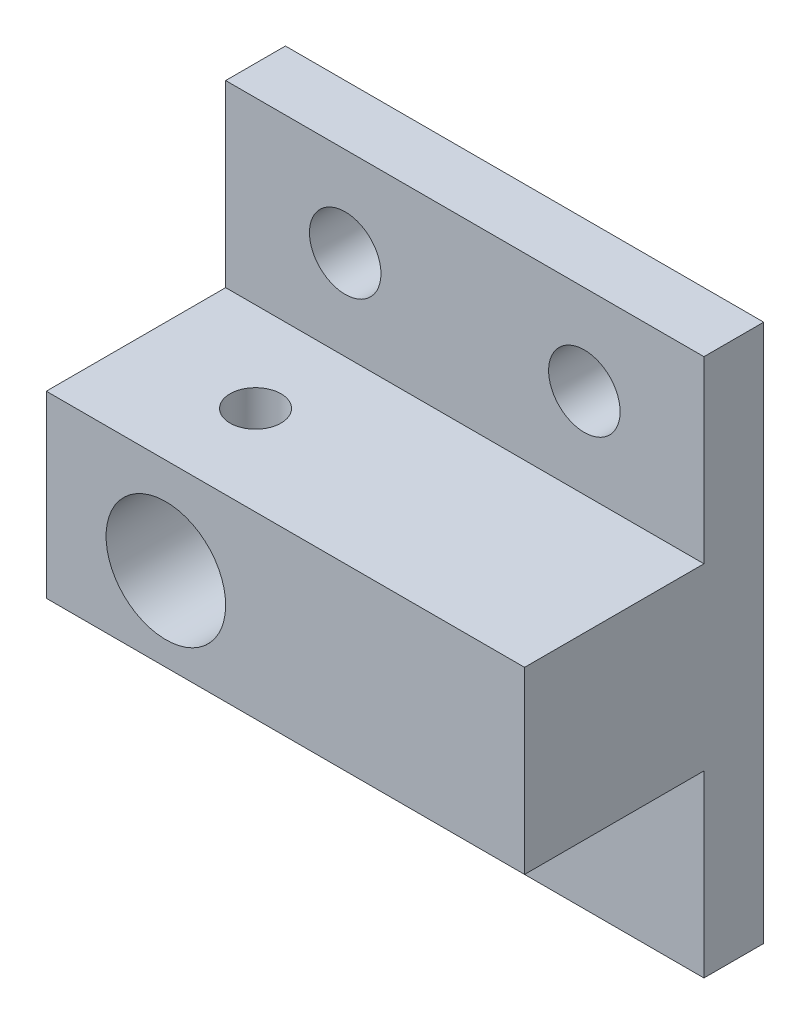
SolidWorks part; units mm, degrees
material "6061 Alloy"
ref_plane "Front Plane" through (0, 0, 0) normal (0, 0, 1) x (1, 0, 0)
ref_plane "Top Plane" through (0, 0, 0) normal (0, 1, 0) x (1, 0, 0)
ref_plane "Right Plane" through (0, 0, 0) normal (1, 0, 0) x (0, 0, -1)
sketch "Sketch1" plane through (0, 0, 0) normal (0, 0, 1) x (1, 0, 0)
  line L1 (-12.7, -14.2875) -> (12.7, -14.2875)
  line L2 (-12.7, -14.2875) -> (-12.7, 14.2875)
  line L3 (-12.7, 14.2875) -> (12.7, 14.2875)
  line L4 (12.7, -14.2875) -> (12.7, 14.2875)
  line L5 (-12.7, -14.2875) -> (12.7, 14.2875) construction
  line L6 (-12.7, 14.2875) -> (12.7, -14.2875) construction
  point P0 (0, 0)
  dimension "D1" = 25.4
  dimension "D2" = 28.575
extrude "Boss-Extrude1" add sketch "Sketch1" along normal blind 12.7
sketch "Sketch3" plane through (0, 0, 12.7) normal (0, 0, 1) x (1, 0, 0)
  line L0 (0, -55) -> (0, 55) construction
  line L1 (-12.7, 4.7625) -> (12.7, 4.7625)
  line L2 (-12.7, 4.7625) -> (-12.7, 14.2875)
  line L3 (-12.7, 14.2875) -> (12.7, 14.2875)
  line L4 (12.7, 4.7625) -> (12.7, 14.2875)
  line L5 (-12.7, 4.7625) -> (12.7, 14.2875) construction
  line L6 (-12.7, 14.2875) -> (12.7, 4.7625) construction
  line L9 (-12.7, -4.7625) -> (12.7, -4.7625)
  line L10 (-12.7, -4.7625) -> (-12.7, -14.2875)
  line L11 (-12.7, -14.2875) -> (12.7, -14.2875)
  line L12 (12.7, -4.7625) -> (12.7, -14.2875)
  line L13 (-12.7, -4.7625) -> (12.7, -14.2875) construction
  line L14 (-12.7, -14.2875) -> (12.7, -4.7625) construction
  point P0 (0, 9.525)
  point P5 (0, -9.525)
  line M2 (12.7, -14.2875) -> (12.7, 14.2875)
  line M4 (-12.7, 14.2875) -> (-12.7, -14.2875)
  line M5 (-12.7, -14.2875) -> (12.7, -14.2875)
  dimension "D1" = 9.525
  dimension "D2" = 9.525
extrude "Cut-Extrude1" cut sketch "Sketch3" against normal blind 9.525 contours L9 M4 M5 M2 | L1 L4 L3 L2
sketch "Sketch2" plane through (0, 0, 12.7) normal (0, 0, 1) x (1, 0, 0)
  line L2 (-12.7, 4.7625) -> (-12.7, -4.7625) construction
  line L3 (-12.7, 4.7625) -> (12.7, 4.7625) construction
  circle A0 centre (-6.35, -0.3175) radius 3.175
  dimension "D1" = 6.35
  dimension "D2" = 6.35
  dimension "D3" = 5.08
extrude "Cut-Extrude2" cut sketch "Sketch2" against normal through all contours A0
sketch "Sketch4" plane through (0, 4.7625, 0) normal (0, 1, 0) x (1, 0, 0)
  line L0 (-12.7, -3.175) -> (-12.7, -12.7) construction
  point P0 (-6.35, -7.9375)
  point P3 (-12.7, -7.9375)
  dimension "D1" = 6.35
hole_wizard "#6-32 Tapped Hole1" positions "Sketch5" profile "Sketch7" tap size "#6-32" standard "ANSI Inch"
sketch "Sketch5" plane through (0, 4.7625, 0) normal (0, 1, 0) x (1, 0, 0)
  point P0 (-6.35, -7.9375)
sketch "Sketch7" plane through (-6.35, 4.7625, 7.9375) normal (1, 0, 0) x (0, 0, 1)
  line L0 (0, 0) -> (0, 1.905)
  line L1 (0, 1.905) -> (1.3525, 1.905)
  line L2 (1.3525, 1.905) -> (1.3525, 0)
  line L5 (1.3525, 0) -> (0, 0)
  line L11 (0, -6.35) -> (0, 107.95) construction
  dimension "Thru Tap Drill Dia." = 2.7051
  dimension "Thru Tap Drill Depth" = 1.905
cosmetic thread "Hole Thread1" parameters "D2"=3.5052
sketch "Sketch8" plane through (0, 0, 3.175) normal (0, 0, 1) x (1, 0, 0)
  line L0 (-12.7, 4.7625) -> (-12.7, 14.2875) construction
  line L1 (-6.35, 9.525) -> (6.35, 9.525) construction
  line L2 (0, -55) -> (0, 55) construction
  line L4 (-12.7, -4.7625) -> (-12.7, -14.2875) construction
  circle A0 centre (-6.35, -0.3175) radius 3.175 construction
  point P0 (-6.35, 9.525)
  point P1 (6.35, 9.525)
  point P2 (0, 9.525)
  point P6 (-12.7, 9.525)
  point P10 (-6.35, -8.5725)
  dimension "D1" = 12.7
  dimension "D2" = 6.35
  dimension "D3" = 8.255
hole_wizard "#6 Clearance Hole1" positions "Sketch9" profile "Sketch11" hole size "#6" standard "ANSI Inch" end condition up to next
sketch "Sketch9" plane through (0, 0, 3.175) normal (0, 0, 1) x (1, 0, 0)
  point P0 (-6.35, 9.525)
  point P3 (6.35, 9.525)
  point P6 (-6.35, -8.5725)
sketch "Sketch11" plane through (-6.35, 9.525, 3.175) normal (1, 0, 0) x (0, -1, 0)
  line L0 (0, 0) -> (0, 3.175)
  line L1 (0, 3.175) -> (1.8986, 3.175)
  line L2 (1.8986, 3.175) -> (1.8986, 0)
  line L5 (1.8986, 0) -> (0, 0)
  line L11 (0, -6.35) -> (0, 107.95) construction
  dimension "Thru Hole Dia." = 3.7973
  dimension "Thru Hole Depth" = 3.175
